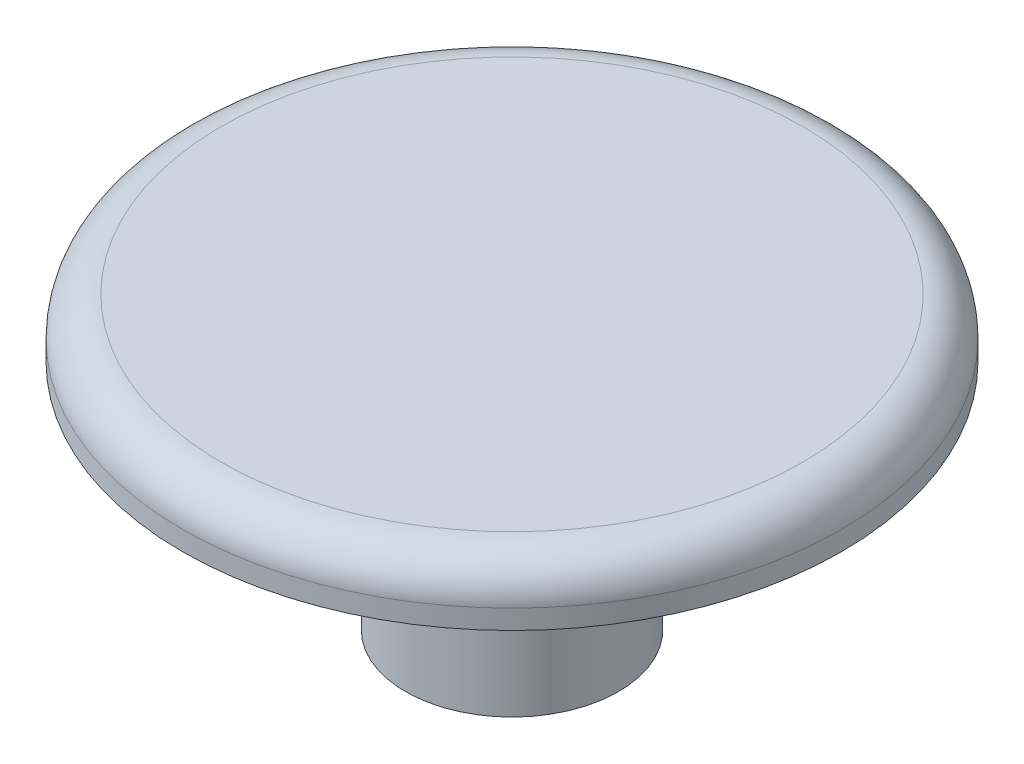
SolidWorks part; units mm, degrees
ref_plane "Front Plane" through (0, 0, 0) normal (0, 0, 1) x (1, 0, 0)
ref_plane "Top Plane" through (0, 0, 0) normal (0, 1, 0) x (1, 0, 0)
ref_plane "Right Plane" through (0, 0, 0) normal (1, 0, 0) x (0, 0, -1)
sketch "Sketch1" plane through (0, 0, 0) normal (0, 0, 1) x (1, 0, 0)
  line L0 (0, 0) -> (0, 77488.0768) construction
  line L1 (0, 0) -> (5.5, 0)
  line L2 (5.5, 0) -> (5.5, 12)
  line L3 (5.5, 12) -> (17, 12)
  line L4 (17, 12) -> (17, 13)
  line L5 (15, 15) -> (0, 15)
  line L6 (0, 0) -> (0, 15)
  arc A0 (17, 13) -> (15, 15) centre (15, 13) ccw
  point P11 (17, 15)
  dimension "D5" = 2
  dimension "D1" = 11
  dimension "D2" = 34
  dimension "D3" = 12
  dimension "D4" = 3
revolve "Revolve1" add sketch "Sketch1" angle 360 about L0
